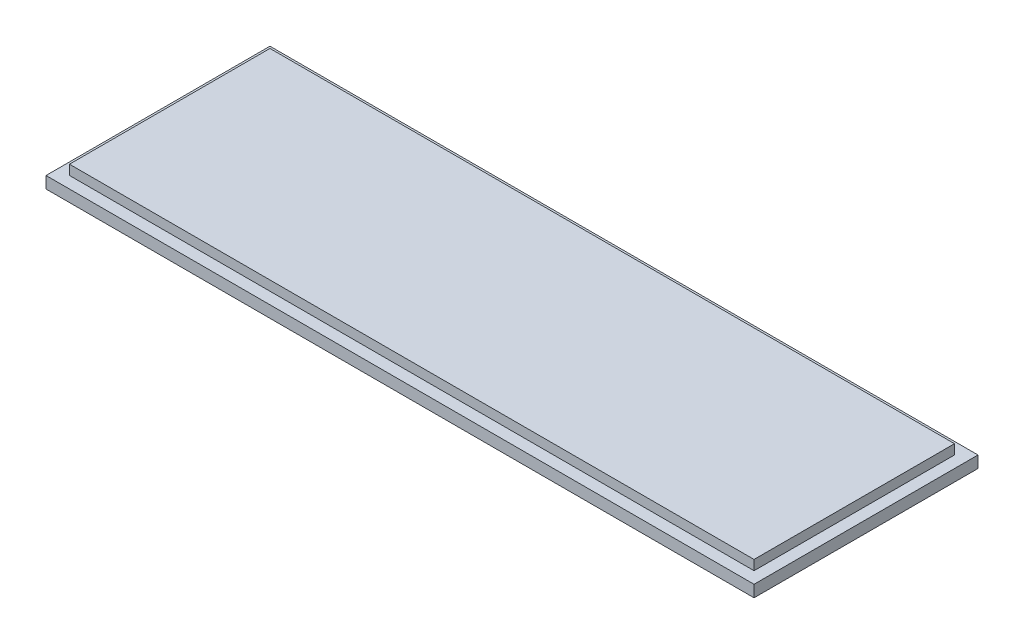
SolidWorks part; units mm, degrees
ref_plane "Přední rovina" through (0, 0, 0) normal (0, 0, 1) x (1, 0, 0)
ref_plane "Horní rovina" through (0, 0, 0) normal (0, 1, 0) x (1, 0, 0)
ref_plane "Pravá rovina" through (0, 0, 0) normal (1, 0, 0) x (0, 0, -1)
sketch "Skica1" plane through (0, 0, 0) normal (0, 1, 0) x (1, 0, 0)
  line L1 (0, 0) -> (72.4, 0)
  line L2 (0, 0) -> (0, 22.9)
  line L3 (0, 22.9) -> (72.4, 22.9)
  line L4 (72.4, 0) -> (72.4, 22.9)
  dimension "D1" = 22.9
  dimension "D2" = 72.4
extrude "Přidat vysunutím2" add sketch "Skica1" along normal blind 1.2
sketch "Skica2" plane through (0, 1.2, 0) normal (0, 1, 0) x (1, 0, 0)
  line L0 (0, 22.9) -> (0, 0) construction
  line L1 (1.2, 21.7) -> (71.2, 21.7)
  line L2 (1.2, 21.7) -> (1.2, 1.2)
  line L3 (1.2, 1.2) -> (71.2, 1.2)
  line L4 (71.2, 21.7) -> (71.2, 1.2)
  line L5 (72.4, 22.9) -> (0, 22.9) construction
  line L6 (72.4, 0) -> (72.4, 22.9) construction
  line L7 (0, 0) -> (72.4, 0) construction
  dimension "D1" = 1.2
  dimension "D2" = 1.2
  dimension "D3" = 1.2
  dimension "D4" = 1.2
extrude "Přidat vysunutím3" add sketch "Skica2" along normal blind 1
